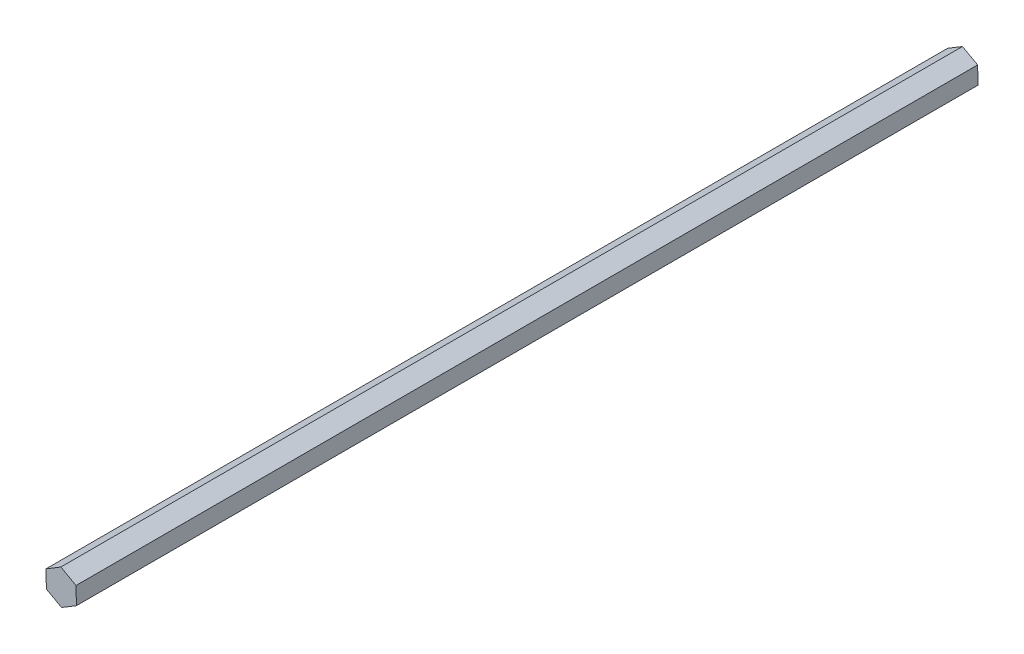
SolidWorks part; units mm, degrees
ref_plane "Front Plane" through (0, 0, 0) normal (0, 0, 1) x (1, 0, 0)
ref_plane "Top Plane" through (0, 0, 0) normal (0, 1, 0) x (1, 0, 0)
ref_plane "Right Plane" through (0, 0, 0) normal (1, 0, 0) x (0, 0, -1)
sketch "Sketch1" plane through (0, 0, 0) normal (0, 0, 1) x (1, 0, 0)
  line L1 (-0.1525, 7.3308) -> (-6.4249, 3.5333)
  line L2 (-6.4249, 3.5333) -> (-6.2724, -3.7974)
  line L3 (-6.2724, -3.7974) -> (0.1525, -7.3308)
  line L4 (0.1525, -7.3308) -> (6.4249, -3.5333)
  line L5 (6.4249, -3.5333) -> (6.2724, 3.7974)
  line L6 (6.2724, 3.7974) -> (-0.1525, 7.3308)
  circle A0 centre (0, 0) radius 6.35 construction
  dimension "D1" = 12.7
extrude "Boss-Extrude1" add sketch "Sketch1" along normal blind 381
